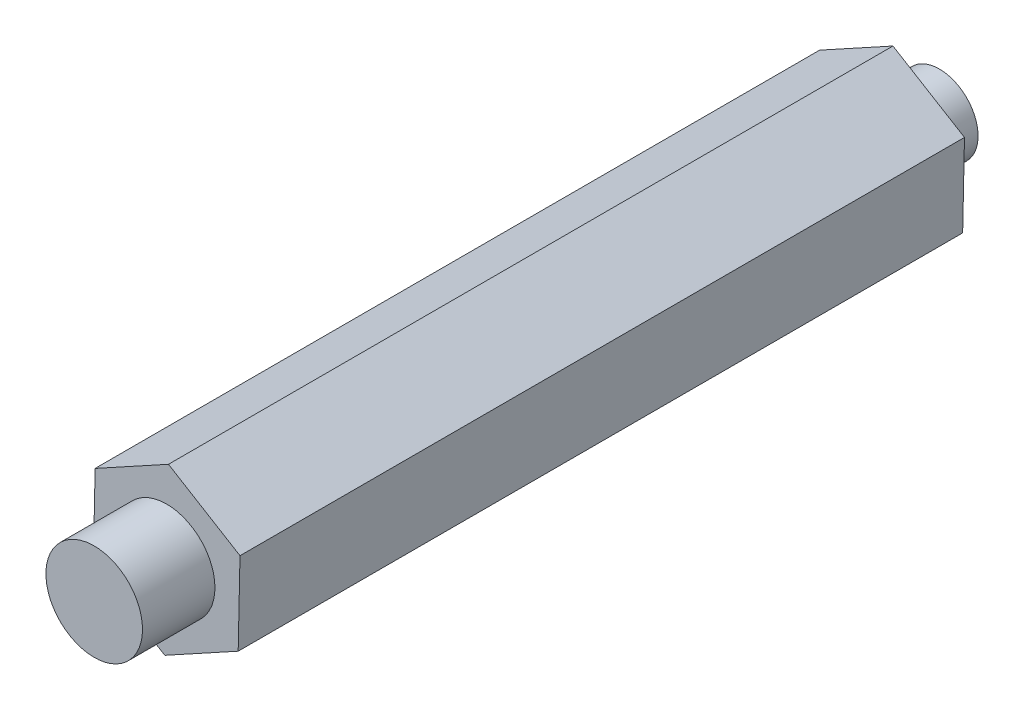
SolidWorks part; units mm, degrees
ref_plane "Front Plane" through (0, 0, 0) normal (0, 0, 1) x (1, 0, 0)
ref_plane "Top Plane" through (0, 0, 0) normal (0, 1, 0) x (1, 0, 0)
ref_plane "Right Plane" through (0, 0, 0) normal (1, 0, 0) x (0, 0, -1)
sketch "Sketch1" plane through (0, 0, 0) normal (0, 0, 1) x (1, 0, 0)
  line L1 (2.9616, -1.7969) -> (3.037, 1.6664)
  line L2 (3.037, 1.6664) -> (0.0754, 3.4633)
  line L3 (0.0754, 3.4633) -> (-2.9616, 1.7969)
  line L4 (-2.9616, 1.7969) -> (-3.037, -1.6664)
  line L5 (-3.037, -1.6664) -> (-0.0754, -3.4633)
  line L6 (-0.0754, -3.4633) -> (2.9616, -1.7969)
  circle A0 centre (0, 0) radius 3 construction
  dimension "D1" = 6
extrude "Boss-Extrude1" add sketch "Sketch1" along normal blind 30
sketch "Sketch2" plane through (0, 0, 30) normal (0, 0, 1) x (1, 0, 0)
  circle A0 centre (0, 0) radius 2
  dimension "D1" = 4
extrude "Boss-Extrude2" add sketch "Sketch2" along normal blind 3
sketch "Sketch3" plane through (0, 0, 0) normal (0, 0, -1) x (-1, 0, 0)
  circle A0 centre (0, 0) radius 1.6
  dimension "D1" = 3.2
extrude "Boss-Extrude3" add sketch "Sketch3" along normal blind 2
